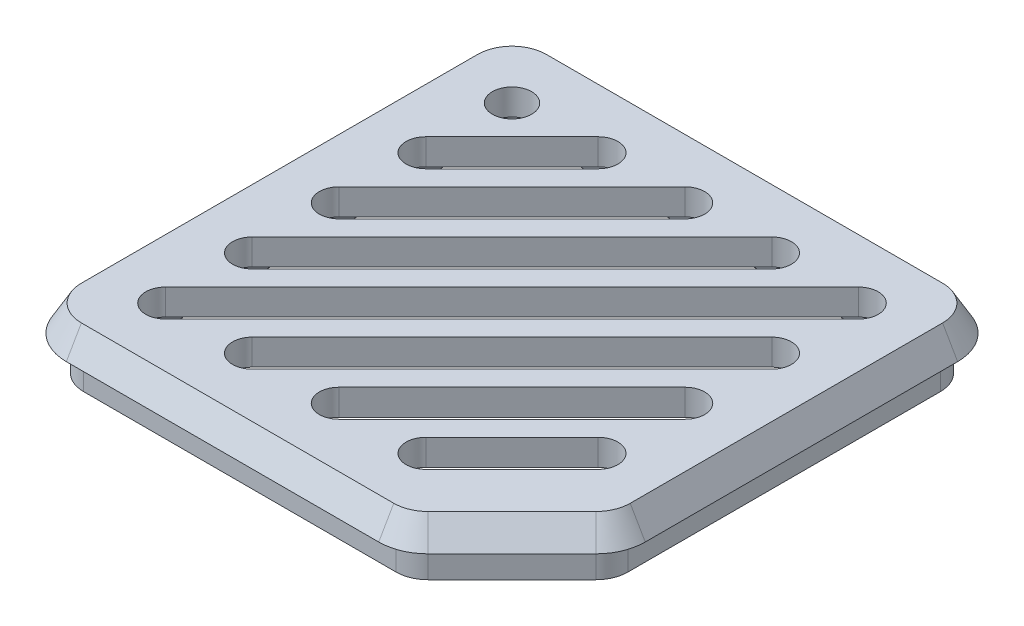
SolidWorks part; units mm, degrees
ref_plane "前视基准面" through (0, 0, 0) normal (0, 0, 1) x (1, 0, 0)
ref_plane "上视基准面" through (0, 0, 0) normal (0, 1, 0) x (1, 0, 0)
ref_plane "右视基准面" through (0, 0, 0) normal (1, 0, 0) x (0, 0, -1)
other "Configuration Table"
sketch "草图1" plane through (0, 0, 0) normal (0, 1, 0) x (1, 0, 0)
  line L5 (-65.3144, 17.3) -> (-88.1428, 17.3)
  line L6 (-88.9928, 16.45) -> (-88.9928, -6.3784)
  line L7 (-88.1428, -7.2284) -> (-70.1428, -7.2284)
  line L8 (-69.5418, -6.9795) -> (-64.7133, -2.151)
  line L9 (-64.4644, -1.55) -> (-64.4644, 16.45)
  line L10 (-65.3144, 18.3) -> (-88.1428, 18.3)
  line L11 (-63.4644, -1.55) -> (-63.4644, 16.45)
  line L12 (-68.8347, -7.6866) -> (-64.0062, -2.8581)
  line L13 (-88.1428, -8.2284) -> (-70.1428, -8.2284)
  line L14 (-89.9928, 16.45) -> (-89.9928, -6.3784)
  line L15 (-65.3144, 18.3) -> (-88.1428, 18.3)
  line L16 (-63.4644, -1.55) -> (-63.4644, 16.45)
  line L17 (-68.8347, -7.6866) -> (-64.0062, -2.8581)
  line L18 (-88.1428, -8.2284) -> (-70.1428, -8.2284)
  line L19 (-89.9928, 16.45) -> (-89.9928, -6.3784)
  arc A5 (-88.1428, 17.3) -> (-88.9928, 16.45) centre (-88.1428, 16.45) ccw
  arc A6 (-88.9928, -6.3784) -> (-88.1428, -7.2284) centre (-88.1428, -6.3784) ccw
  arc A7 (-70.1428, -7.2284) -> (-69.5418, -6.9795) centre (-70.1428, -6.3784) ccw
  arc A8 (-64.7133, -2.151) -> (-64.4644, -1.55) centre (-65.3144, -1.55) ccw
  arc A9 (-64.4644, 16.45) -> (-65.3144, 17.3) centre (-65.3144, 16.45) ccw
  arc A10 (-63.4644, 16.45) -> (-65.3144, 18.3) centre (-65.3144, 16.45) ccw
  arc A11 (-64.0062, -2.8581) -> (-63.4644, -1.55) centre (-65.3144, -1.55) ccw
  arc A12 (-70.1428, -8.2284) -> (-68.8347, -7.6866) centre (-70.1428, -6.3784) ccw
  arc A13 (-89.9928, -6.3784) -> (-88.1428, -8.2284) centre (-88.1428, -6.3784) ccw
  arc A14 (-88.1428, 18.3) -> (-89.9928, 16.45) centre (-88.1428, 16.45) ccw
  arc A15 (-63.4644, 16.45) -> (-65.3144, 18.3) centre (-65.3144, 16.45) ccw
  arc A16 (-64.0062, -2.8581) -> (-63.4644, -1.55) centre (-65.3144, -1.55) ccw
  arc A17 (-70.1428, -8.2284) -> (-68.8347, -7.6866) centre (-70.1428, -6.3784) ccw
  arc A18 (-89.9928, -6.3784) -> (-88.1428, -8.2284) centre (-88.1428, -6.3784) ccw
  arc A19 (-88.1428, 18.3) -> (-89.9928, 16.45) centre (-88.1428, 16.45) ccw
  dimension "D1" = 0.15
  dimension "D2" = 1
extrude "凸台-拉伸1" add sketch "草图1" against normal blind 2
sketch "草图2" plane through (0, 0, 0) normal (0, 1, 0) x (1, 0, 0)
  line L10 (-65.3144, 19.3) -> (-88.1428, 19.3)
  line L11 (-90.9928, 16.45) -> (-90.9928, -6.3784)
  line L12 (-88.1428, -9.2284) -> (-70.1428, -9.2284)
  line L13 (-68.1275, -8.3937) -> (-63.2991, -3.5653)
  line L14 (-62.4644, -1.55) -> (-62.4644, 16.45)
  line L15 (-65.3144, 19.3) -> (-88.1428, 19.3)
  line L16 (-90.9928, 16.45) -> (-90.9928, -6.3784)
  line L17 (-88.1428, -9.2284) -> (-70.1428, -9.2284)
  line L18 (-68.1275, -8.3937) -> (-63.2991, -3.5653)
  line L19 (-62.4644, -1.55) -> (-62.4644, 16.45)
  arc A10 (-62.4644, 16.45) -> (-65.3144, 19.3) centre (-65.3144, 16.45) ccw
  arc A11 (-88.1428, 19.3) -> (-90.9928, 16.45) centre (-88.1428, 16.45) ccw
  arc A12 (-90.9928, -6.3784) -> (-88.1428, -9.2284) centre (-88.1428, -6.3784) ccw
  arc A13 (-70.1428, -9.2284) -> (-68.1275, -8.3937) centre (-70.1428, -6.3784) ccw
  arc A14 (-63.2991, -3.5653) -> (-62.4644, -1.55) centre (-65.3144, -1.55) ccw
  arc A15 (-62.4644, 16.45) -> (-65.3144, 19.3) centre (-65.3144, 16.45) ccw
  arc A16 (-88.1428, 19.3) -> (-90.9928, 16.45) centre (-88.1428, 16.45) ccw
  arc A17 (-90.9928, -6.3784) -> (-88.1428, -9.2284) centre (-88.1428, -6.3784) ccw
  arc A18 (-70.1428, -9.2284) -> (-68.1275, -8.3937) centre (-70.1428, -6.3784) ccw
  arc A19 (-63.2991, -3.5653) -> (-62.4644, -1.55) centre (-65.3144, -1.55) ccw
  dimension "D1" = 1
extrude "凸台-拉伸2" add sketch "草图2" along normal blind 1.5 draft 30 contours A15 L15 A16 L16 A17 L17 A18 L18 A19 L19
sketch "草图3" plane through (0, 0, 0) normal (0, -1, 0) x (1, 0, 0)
  line L5 (-86.7128, -10.0516) -> (-81.7444, -15.02) construction
  line L6 (-85.913, -9.2518) -> (-80.9446, -14.2202)
  line L7 (-87.5126, -10.8513) -> (-82.5441, -15.8198)
  line L8 (-71.7128, 4.9484) -> (-66.7444, -0.02) construction
  line L9 (-70.913, 5.7482) -> (-65.9446, 0.7798)
  line L10 (-66.7444, -15.02) -> (-66.7444, 0.9577)
  line L11 (-66.7444, 0.9577) -> (-70.7351, 4.9484)
  line L12 (-70.7351, 4.9484) -> (-86.7128, 4.9484)
  line L13 (-86.7128, 4.9484) -> (-86.7128, -15.02)
  line L14 (-86.7128, -15.02) -> (-66.7444, -15.02)
  line L15 (-66.7444, -15.02) -> (-66.7444, 0.9577) construction
  line L16 (-66.7444, 0.9577) -> (-70.7351, 4.9484) construction
  line L17 (-70.7351, 4.9484) -> (-86.7128, 4.9484) construction
  line L18 (-86.7128, 4.9484) -> (-86.7128, -15.02) construction
  line L19 (-86.7128, -15.02) -> (-66.7444, -15.02) construction
  line L20 (-72.5126, 4.1487) -> (-67.5441, -0.8198)
  line L22 (-69.5418, 6.9795) -> (-64.7133, 2.151) construction
  line L23 (-76.7128, 4.9484) -> (-66.7444, -5.02) construction
  line L24 (-75.913, 5.7482) -> (-65.9446, -4.2202)
  line L25 (-77.5126, 4.1487) -> (-67.5441, -5.8198)
  line L26 (-81.7128, 4.9484) -> (-66.7444, -10.02) construction
  line L27 (-80.913, 5.7482) -> (-65.9446, -9.2202)
  line L28 (-82.5126, 4.1487) -> (-67.5441, -10.8198)
  line L29 (-86.7128, -0.0516) -> (-71.7444, -15.02) construction
  line L30 (-85.913, 0.7482) -> (-70.9446, -14.2202)
  line L31 (-87.5126, -0.8513) -> (-72.5441, -15.8198)
  line L32 (-86.7128, 4.9484) -> (-66.7444, -15.02) construction
  line L33 (-85.913, 5.7482) -> (-65.9446, -14.2202)
  line L34 (-87.5126, 4.1487) -> (-67.5441, -15.8198)
  line L35 (-86.7128, -5.0516) -> (-76.7444, -15.02) construction
  line L36 (-85.913, -4.2518) -> (-75.9446, -14.2202)
  line L37 (-87.5126, -5.8513) -> (-77.5441, -15.8198)
  arc A5 (-85.913, -9.2518) -> (-87.5126, -10.8513) centre (-86.7128, -10.0516) ccw
  arc A6 (-82.5441, -15.8198) -> (-80.9446, -14.2202) centre (-81.7444, -15.02) ccw
  arc A7 (-70.913, 5.7482) -> (-72.5126, 4.1487) centre (-71.7128, 4.9484) ccw
  arc A8 (-67.5441, -0.8198) -> (-65.9446, 0.7798) centre (-66.7444, -0.02) ccw
  arc A9 (-75.913, 5.7482) -> (-77.5126, 4.1487) centre (-76.7128, 4.9484) ccw
  arc A10 (-67.5441, -5.8198) -> (-65.9446, -4.2202) centre (-66.7444, -5.02) ccw
  arc A11 (-80.913, 5.7482) -> (-82.5126, 4.1487) centre (-81.7128, 4.9484) ccw
  arc A12 (-67.5441, -10.8198) -> (-65.9446, -9.2202) centre (-66.7444, -10.02) ccw
  arc A13 (-85.913, 0.7482) -> (-87.5126, -0.8513) centre (-86.7128, -0.0516) ccw
  arc A14 (-72.5441, -15.8198) -> (-70.9446, -14.2202) centre (-71.7444, -15.02) ccw
  arc A15 (-85.913, 5.7482) -> (-87.5126, 4.1487) centre (-86.7128, 4.9484) ccw
  arc A16 (-67.5441, -15.8198) -> (-65.9446, -14.2202) centre (-66.7444, -15.02) ccw
  arc A17 (-85.913, -4.2518) -> (-87.5126, -5.8513) centre (-86.7128, -5.0516) ccw
  arc A18 (-77.5441, -15.8198) -> (-75.9446, -14.2202) centre (-76.7444, -15.02) ccw
  circle A19 centre (-86.7128, -15.02) radius 1.131
  point P2 (-84.2286, -12.5358)
  point P7 (-69.2286, 2.4642)
  point P20 (-71.7286, -0.0358)
  point P27 (-74.2286, -2.5358)
  point P35 (-79.2286, -7.5358)
  point P42 (-76.7286, -5.0358)
  point P47 (-81.7286, -10.0358)
  dimension "D2" = 5
  dimension "D3" = 5
  dimension "D4" = 5
  dimension "D5" = 5
  dimension "D6" = 5
  dimension "D7" = 5
  dimension "D1" = 2.28
extrude "切除-拉伸1" cut sketch "草图3" against normal up to next
